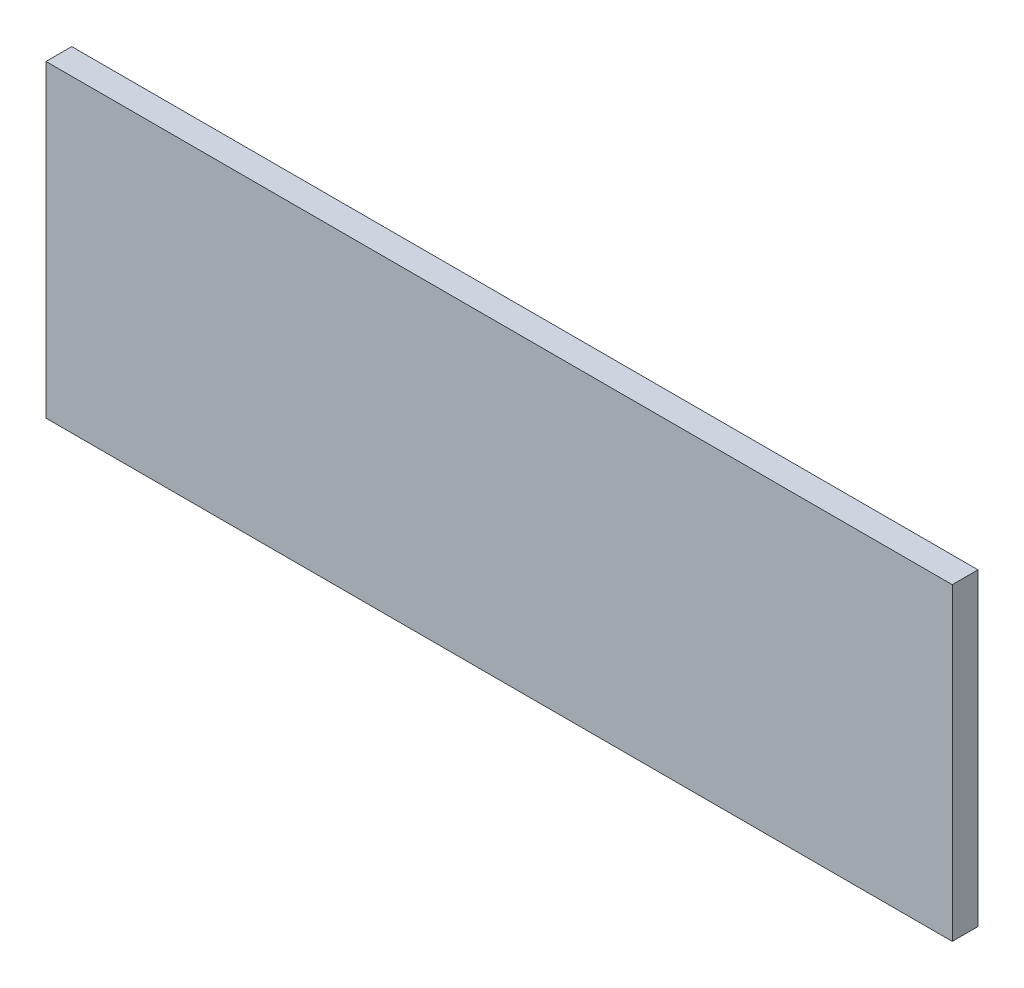
SolidWorks part; units mm, degrees
ref_plane "Front Plane" through (0, 0, 0) normal (0, 0, 1) x (1, 0, 0)
ref_plane "Top Plane" through (0, 0, 0) normal (0, 1, 0) x (1, 0, 0)
ref_plane "Right Plane" through (0, 0, 0) normal (1, 0, 0) x (0, 0, -1)
sketch "Sketch1" plane through (0, 0, 0) normal (0, 0, 1) x (1, 0, 0)
  line L1 (-88, -30) -> (88, -30)
  line L2 (-88, -30) -> (-88, 30)
  line L3 (-88, 30) -> (88, 30)
  line L4 (88, -30) -> (88, 30)
  line L5 (-88, -30) -> (88, 30) construction
  line L6 (-88, 30) -> (88, -30) construction
  point P0 (0, 0)
  dimension "D1" = 176
  dimension "D2" = 60
extrude "Boss-Extrude1" add sketch "Sketch1" along normal blind 5
